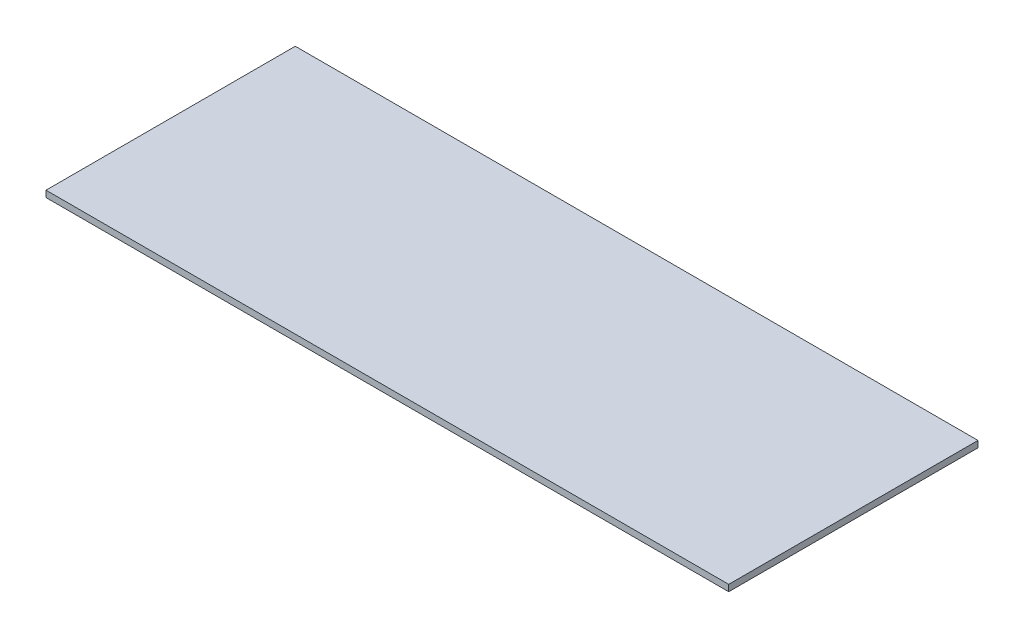
SolidWorks part; units mm, degrees
ref_plane "Front Plane" through (0, 0, 0) normal (0, 0, 1) x (1, 0, 0)
ref_plane "Top Plane" through (0, 0, 0) normal (0, 1, 0) x (1, 0, 0)
ref_plane "Right Plane" through (0, 0, 0) normal (1, 0, 0) x (0, 0, -1)
sketch "Sketch1" plane through (0, 0, 0) normal (0, 1, 0) x (1, 0, 0)
  line L1 (-59.1289, 156.3918) -> (446.9711, 156.3918)
  line L2 (-59.1289, 156.3918) -> (-59.1289, -28.4005)
  line L3 (-59.1289, -28.4005) -> (446.9711, -28.4005)
  line L4 (446.9711, 156.3918) -> (446.9711, -28.4005)
  dimension "D1" = 506.1
  dimension "D2" = 184.7924
extrude "Boss-Extrude2" add sketch "Sketch1" along normal blind 4.7625
